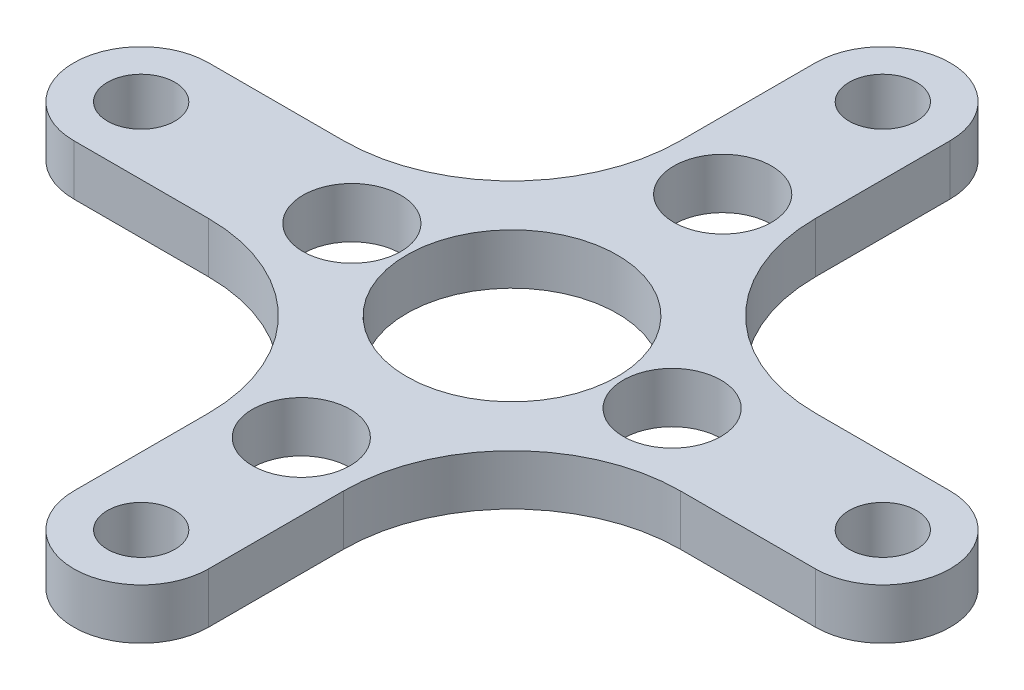
SolidWorks part; units mm, degrees
ref_plane "Ön Düzlem" through (0, 0, 0) normal (0, 0, 1) x (1, 0, 0)
ref_plane "Üst Düzlem" through (0, 0, 0) normal (0, 1, 0) x (1, 0, 0)
ref_plane "Sağ Düzlem" through (0, 0, 0) normal (1, 0, 0) x (0, 0, -1)
sketch "Çizim2" plane through (0, 0, 0) normal (0, 1, 0) x (1, 0, 0)
  line L0 (-22, 0) -> (22, 0) construction
  line L1 (0, 22) -> (0, -22) construction
  line L2 (-9.5, 22) -> (-9.5, -22) construction
  line L3 (9.5, 22) -> (9.5, -22) construction
  line L4 (-22, -12.5) -> (22, -12.5) construction
  line L5 (-22, 12.5) -> (22, 12.5) construction
  line L7 (-4, 22) -> (-4, 14)
  line L8 (4, 22) -> (4, 14)
  line L9 (22, -4) -> (14, -4)
  line L10 (-4, -22) -> (-4, -14)
  line L11 (22, -4) -> (14, -4)
  line L12 (22, 4) -> (14, 4)
  line L13 (-4, -22) -> (-4, -14)
  line L14 (4, -22) -> (4, -14)
  line L15 (-22, 4) -> (-14, 4)
  line L16 (-22, -4) -> (-14, -4)
  arc A0 (-22, 4) -> (-18, 0) centre (-22, 0) ccw
  circle A1 centre (-22, 0) radius 2
  circle A2 centre (22, 0) radius 2
  circle A3 centre (22, 0) radius 4
  arc A4 (-4, -22) -> (4, -22) centre (0, -22) ccw
  circle A5 centre (0, -22) radius 2
  circle A6 centre (0, 22) radius 2
  arc A7 (-4, 22) -> (3.7109, 20.507) centre (0, 22) cw
  circle A8 centre (0, 0) radius 6.25
  circle A9 centre (9.5, 0) radius 2
  circle A10 centre (9.5, 0) radius 2.9
  circle A11 centre (-9.5, 0) radius 2
  circle A12 centre (-9.5, 0) radius 2.9
  circle A13 centre (0, 12.5) radius 2
  circle A14 centre (0, 12.5) radius 2.9
  circle A15 centre (0, -12.5) radius 2.9
  circle A16 centre (0, -12.5) radius 2
  arc A18 (-4, 14) -> (-14, 4) centre (-14, 14) cw
  arc A19 (4, 14) -> (14, 4) centre (14, 14) ccw
  arc A20 (-4, -14) -> (-14, -4) centre (-14, -14) ccw
  arc A21 (4, -14) -> (14, -4) centre (14, -14) cw
  point P4 (0, 0)
  point P8 (0, 0)
  point P60 (0, 0)
  point P71 (0, 0)
  dimension "D2" = 8
  dimension "D3" = 4
  dimension "D4" = 12.5
  dimension "D6" = 5.8
  dimension "D7" = 4
  dimension "D11" = 5.8
  dimension "D12" = 4
  dimension "D13" = 10
  dimension "D1" = 44
  dimension "D8" = 9.5
  dimension "D5" = 9.5
  dimension "D9" = 12.5
  dimension "D10" = 12.5
  dimension "D15" = 4
extrude "Yükseklik-Ekstrüzyon1" add sketch "Çizim2" along normal blind 3
